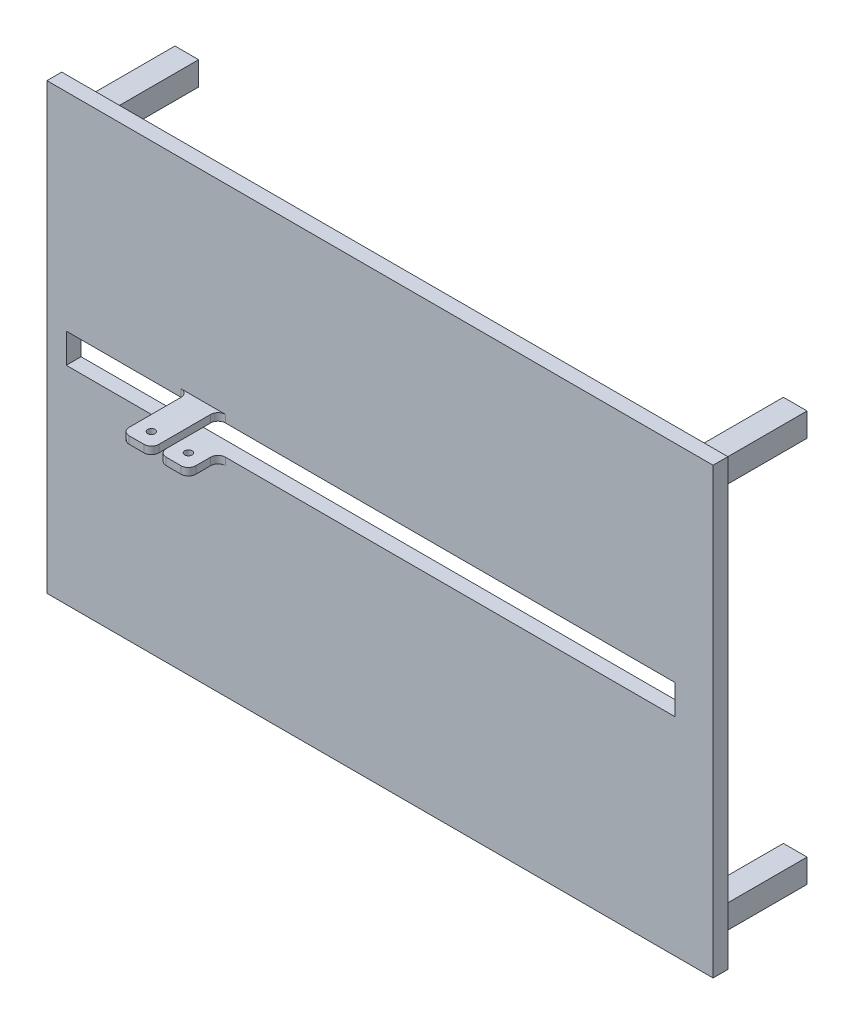
SolidWorks part; units mm, degrees
ref_plane "Front Plane" through (0, 0, 0) normal (0, 0, 1) x (1, 0, 0)
ref_plane "Top Plane" through (0, 0, 0) normal (0, 1, 0) x (1, 0, 0)
ref_plane "Right Plane" through (0, 0, 0) normal (1, 0, 0) x (0, 0, -1)
sketch "Sketch1" plane through (0, 0, 0) normal (0, 0, 1) x (1, 0, 0)
  line L1 (-650, 300) -> (650, 300)
  line L2 (-650, 300) -> (-650, -300)
  line L3 (-650, -300) -> (650, -300)
  line L4 (650, 300) -> (650, -300)
  line L5 (-650, 300) -> (650, -300) construction
  line L6 (-650, -300) -> (650, 300) construction
  line L7 (558.8382, 20) -> (-558.8382, 20)
  line L8 (558.8382, 20) -> (558.8382, -20)
  line L9 (-558.8382, 20) -> (-558.8382, -20)
  line L10 (-558.8382, -20) -> (558.8382, -20)
  point P0 (0, 0)
  point P12 (0, -20)
  dimension "D1" = 600
  dimension "D2" = 1300
extrude "Boss-Extrude1" add sketch "Sketch1" along normal blind 20
sketch "Sketch2" plane through (0, 0, 20) normal (0, 0, 1) x (1, 0, 0)
  line L1 (558.8382, 20) -> (-558.8382, 20) construction
  line L2 (-358.8382, 20) -> (-358.8382, 30)
  line L3 (-358.8382, 30) -> (-318.8382, 30)
  line L4 (-318.8382, 30) -> (-318.8382, 20)
  line L5 (-318.8382, 20) -> (-358.8382, 20)
  line L7 (-318.8382, -30) -> (-318.8382, -20)
  line L8 (-318.8382, -20) -> (-358.8382, -20)
  line L9 (-358.8382, -20) -> (-358.8382, -30)
  line L10 (-358.8382, -30) -> (-318.8382, -30)
  dimension "D1" = 10
  dimension "D2" = 40
extrude "Boss-Extrude2" add sketch "Sketch2" along normal blind 40
sketch "Sketch3" plane through (0, -30, 0) normal (0, -1, 0) x (1, 0, 0)
  circle A0 centre (-338.8382, 40) radius 5
  dimension "D1" = 10
extrude "Cut-Extrude1" cut sketch "Sketch3" against normal blind 10
sketch "Sketch4" plane through (0, 0, 60) normal (0, 0, 1) x (1, 0, 0)
  line L0 (-358.8382, 30) -> (-318.8382, 30)
  line L1 (-318.8382, 30) -> (-318.8382, 20)
  line L2 (-318.8382, 20) -> (-358.8382, 20)
  line L3 (-358.8382, 20) -> (-358.8382, 30)
extrude "Boss-Extrude3" add sketch "Sketch4" along normal blind 50
sketch "Sketch5" plane through (0, 20, 0) normal (0, -1, 0) x (1, 0, 0)
  circle A0 centre (-338.8382, 90) radius 5
  dimension "D2" = 10
extrude "Cut-Extrude2" cut sketch "Sketch5" against normal blind 10
fillet "Fillet1" radius 10 1 edges at (-318.8382, -25, 20)
fillet "Fillet2" radius 10 1 edges at (-318.8382, 25, 20)
fillet "Fillet3" radius 10 1 edges at (-358.8382, -25, 20)
fillet "Fillet4" radius 10 1 edges at (-358.8382, 25, 20)
fillet "Fillet5" radius 10 1 edges at (-318.8382, -25, 60)
fillet "Fillet6" radius 10 1 edges at (-358.8382, -25, 60)
fillet "Fillet7" radius 10 1 edges at (-358.8382, 25, 110)
fillet "Fillet8" radius 10 1 edges at (-318.8382, 25, 110)
sketch "Sketch6" plane through (558.8382, 0, 0) normal (-1, 0, 0) x (0, 0, 1)
  line L0 (0, 20) -> (20, 20)
  line L1 (20, 20) -> (20, -20)
  line L2 (20, -20) -> (0, -20)
  line L3 (0, 300) -> (0, -300) construction
  line L4 (0, -20) -> (0, 20)
extrude "Boss-Extrude4" add sketch "Sketch6" along normal blind 260
sketch "Sketch7" plane through (-558.8382, 0, 0) normal (1, 0, 0) x (0, 0, -1)
  line L0 (-20, 20) -> (0, 20)
  line L1 (0, 20) -> (0, -20)
  line L2 (0, -20) -> (-20, -20)
  line L3 (-20, -20) -> (-20, 20)
extrude "Boss-Extrude5" add sketch "Sketch7" along normal blind 35
sketch "Sketch8" plane through (-650, 0, 0) normal (-1, 0, 0) x (0, 0, 1)
  line L0 (20, 300) -> (20, -300)
  line L1 (20, -300) -> (0, -300)
  line L2 (0, -300) -> (0, 300)
  line L3 (0, 300) -> (20, 300)
extrude "Cut-Extrude3" cut sketch "Sketch8" against normal blind 100
sketch "Sketch9" plane through (650, 0, 0) normal (1, 0, 0) x (0, 0, -1)
  line L0 (-20, -300) -> (-20, 300)
  line L1 (-20, 300) -> (0, 300)
  line L2 (0, 300) -> (0, -300)
  line L3 (0, -300) -> (-20, -300)
extrude "Cut-Extrude4" cut sketch "Sketch9" against normal blind 300
sketch "Sketch10" plane through (0, 0, 0) normal (0, 0, -1) x (-1, 0, 0)
  line L1 (527, -277) -> (495, -277)
  line L4 (524, -274) -> (498, -274)
  line L5 (498, -274) -> (498, -248)
  line L6 (498, -248) -> (524, -248)
  line L7 (524, -248) -> (524, -274)
  line L8 (495, -277) -> (495, -245)
  line L9 (495, -245) -> (527, -245)
  line L10 (527, -245) -> (527, -277)
  line L13 (-295, -245) -> (-327, -245)
  line L14 (-298, -248) -> (-324, -248)
  line L15 (-298, -274) -> (-298, -248)
  line L16 (-295, -277) -> (-295, -245)
  line L17 (-327, -277) -> (-295, -277)
  line L18 (-324, -274) -> (-298, -274)
  line L19 (-324, -248) -> (-324, -274)
  line L20 (-327, -245) -> (-327, -277)
  line L23 (-295, 245) -> (-327, 245)
  line L24 (-298, 248) -> (-324, 248)
  line L25 (-327, 245) -> (-327, 277)
  line L26 (-324, 248) -> (-324, 274)
  line L27 (-327, 277) -> (-295, 277)
  line L28 (-324, 274) -> (-298, 274)
  line L29 (-298, 274) -> (-298, 248)
  line L30 (-295, 277) -> (-295, 245)
  line L31 (495, 245) -> (527, 245)
  line L32 (498, 248) -> (524, 248)
  line L33 (495, 277) -> (495, 245)
  line L34 (498, 274) -> (498, 248)
  line L35 (524, 274) -> (498, 274)
  line L36 (527, 277) -> (495, 277)
  line L37 (524, 248) -> (524, 274)
  line L38 (527, 245) -> (527, 277)
extrude "Boss-Extrude6" add sketch "Sketch10" along normal blind 130
